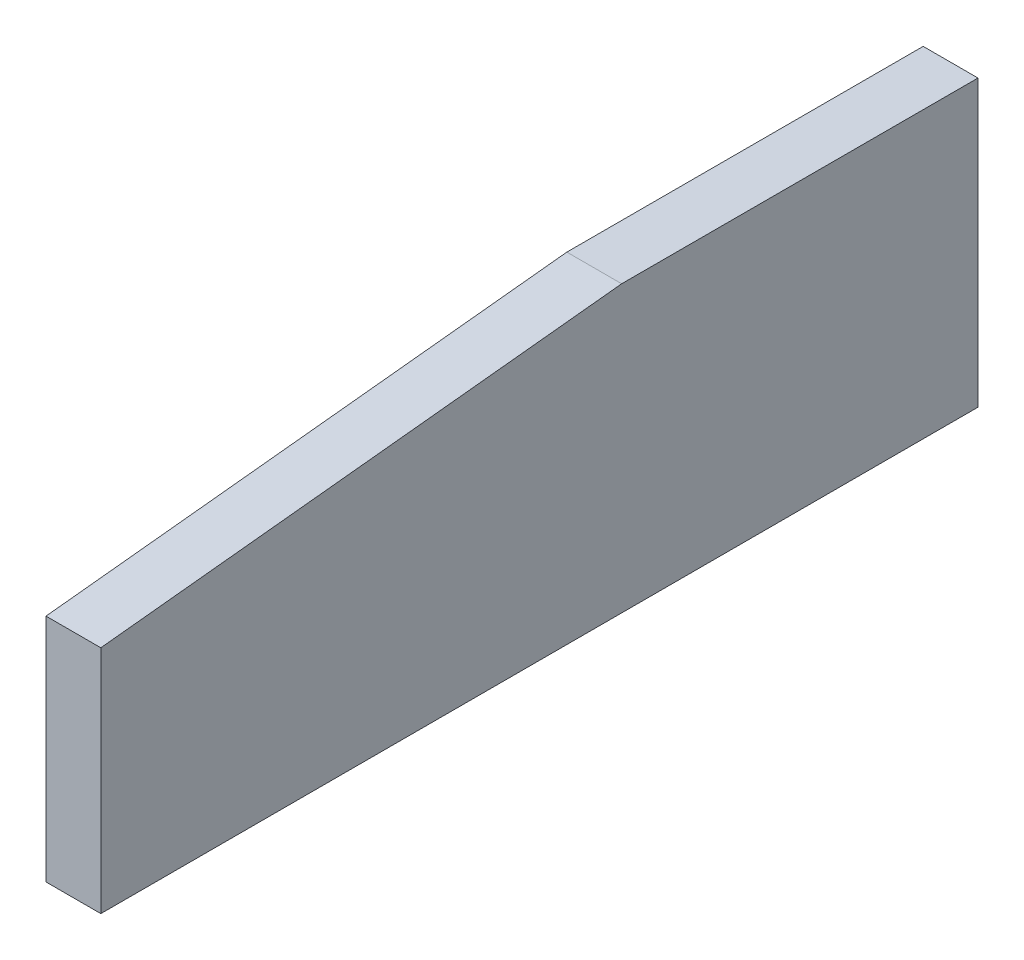
SolidWorks part; units mm, degrees
material "Mahogany"
ref_plane "Front Plane" through (0, 0, 0) normal (0, 0, 1) x (1, 0, 0)
ref_plane "Top Plane" through (0, 0, 0) normal (0, 1, 0) x (1, 0, 0)
ref_plane "Right Plane" through (0, 0, 0) normal (1, 0, 0) x (0, 0, -1)
sketch "Sketch1" plane through (0, 0, 0) normal (1, 0, 0) x (0, 0, -1)
  line L0 (-106.3396, 25.1321) -> (-106.3396, -16.8679)
  line L1 (-106.3396, -16.8679) -> (53.6604, -16.8679)
  line L2 (53.6604, -16.8679) -> (53.6604, 35.1321)
  line L3 (53.6604, 35.1321) -> (-11.3396, 35.1321)
  line L4 (-11.3396, 35.1321) -> (-106.3396, 25.1321)
  dimension "D1" = 42
  dimension "D2" = 52
  dimension "D3" = 160
  dimension "D4" = 65
extrude "Boss-Extrude1" add sketch "Sketch1" along normal blind 10
sketch "Sketch2" plane through (0, 0, 0) normal (-1, 0, 0) x (0, 0, 1)
  line L0 (106.3396, 25.1321) -> (106.3396, -16.8679) construction
  line L1 (106.3396, -16.8679) -> (-53.6604, -16.8679) construction
  line L2 (-53.6604, 35.1321) -> (11.3396, 35.1321) construction
  line L3 (-53.6604, -16.8679) -> (-53.6604, 35.1321) construction
  line L8 (-53.6604, 35.1321) -> (11.3396, 35.1321) construction
  circle A0 centre (101.3396, -7.8679) radius 2
  circle A1 centre (101.3396, 20.1321) radius 2
  circle A2 centre (-48.6604, -7.8679) radius 2
  circle A3 centre (-48.6604, 20.1321) radius 2
  dimension "D1" = 4
  dimension "D4" = 4
  dimension "D7" = 4
  dimension "D9" = 4
  dimension "D2" = 5
  dimension "D3" = 9
  dimension "D5" = 15
  dimension "D8" = 5
  dimension "D10" = 15
extrude "Cut-Extrude1" cut sketch "Sketch2" against normal blind 5
